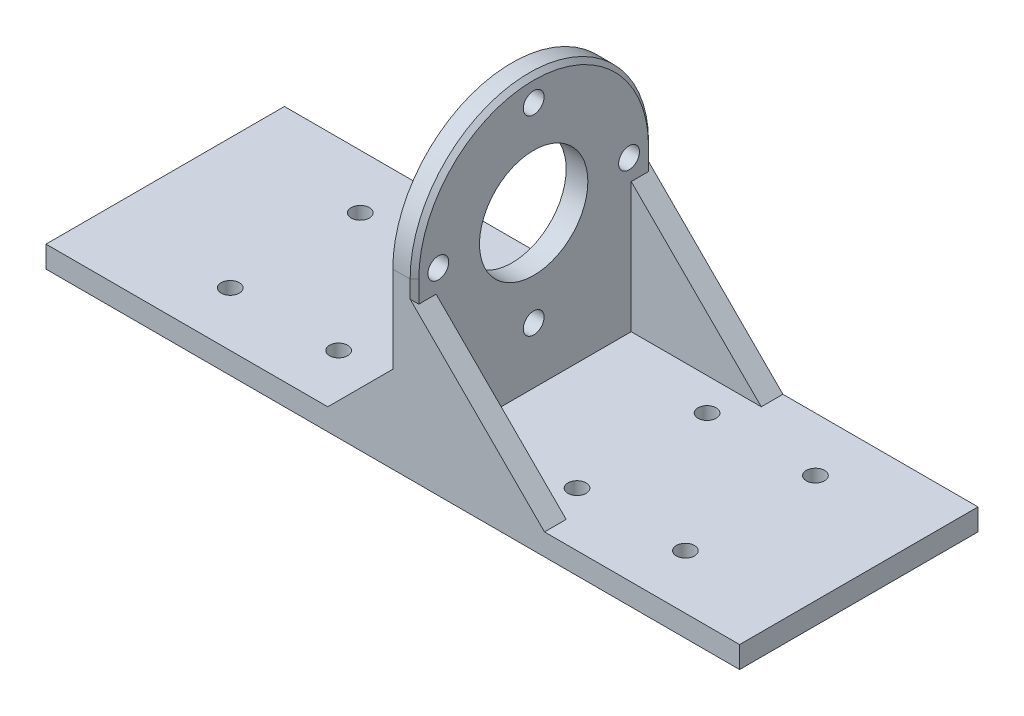
SolidWorks part; units mm, degrees
ref_plane "Front" through (0, 0, 0) normal (0, 0, 1) x (1, 0, 0)
ref_plane "Top" through (0, 0, 0) normal (0, 1, 0) x (1, 0, 0)
ref_plane "Right" through (0, 0, 0) normal (1, 0, 0) x (0, 0, -1)
sketch "草图1" plane through (0, 0, 0) normal (1, 0, 0) x (0, 0, -1)
  line L0 (-27.5, 0) -> (-27.5, -40)
  line L1 (-27.5, -40) -> (27.5, -40)
  line L2 (27.5, -40) -> (27.5, 0)
  arc A0 (27.5, 0) -> (-27.5, 0) centre (0, 0) ccw
  circle A1 centre (0, 0) radius 22 construction
  circle A2 centre (0, 0) radius 12.5
  circle A3 centre (0, 22) radius 2.4
  circle A4 centre (22, 0) radius 2.4
  circle A5 centre (0, -22) radius 2.4
  circle A6 centre (-22, 0) radius 2.4
extrude "凸台-拉伸1" add sketch "草图1" along normal blind 5
sketch "草图2" plane through (0, 0, 0) normal (-1, 0, 0) x (0, 0, 1)
  line L0 (27.5, 0) -> (27.5, -40) construction
  line L1 (-27.5, -40) -> (27.5, -40)
  line L2 (-27.5, -40) -> (-27.5, -35)
  line L3 (-27.5, -35) -> (27.5, -35)
  line L4 (27.5, -40) -> (27.5, -35)
  line L5 (0, -35) -> (0, -40) construction
  line L6 (-27.5, -37.5) -> (27.5, -37.5) construction
  point P112 (0, -37.5)
extrude "凸台-拉伸2" add sketch "草图2" along normal blind 80 contours L3 L4 L1 L2
sketch3d "3D草图1" plane through (0, 0, 0) normal (0, 0, 1) x (1, 0, 0)
  dimension "D1" = 25
sketch "草图3" plane through (0, 0, 25) normal (0, 0, 1) x (1, 0, 0)
  line L0 (0, -35) -> (0, -20) construction
  line L1 (0, 0) -> (0, -35) construction
  line L2 (0, -35) -> (-15, -35) construction
  line L3 (-80, -35) -> (0, -35) construction
  line L4 (-15, -35) -> (0, -20)
  dimension "D1" = 15
  dimension "D2" = 15
rib "筋1" sketch "草图3" sketch "草图3" thickness 5 extrusion direction parallel to sketch draft on no parameters "D1"=5
mirror "镜向1" about plane through (0, 0, 0) normal (0, 0, 1) of "筋1"
chamfer "倒角2" distance 5 angle 45 1 edges at (0, -35, 0)
sketch "草图4" plane through (5, 0, 0) normal (1, 0, 0) x (0, 0, -1)
  line L0 (27.5, -40) -> (27.5, 0) construction
  line L1 (-27.5, -40) -> (27.5, -40)
  line L2 (-27.5, -40) -> (-27.5, -35)
  line L3 (-27.5, -35) -> (27.5, -35)
  line L4 (27.5, -40) -> (27.5, -35)
  line L5 (0, -35) -> (0, -40) construction
  line L6 (-27.5, -37.5) -> (27.5, -37.5) construction
  point P160 (0, -37.5)
extrude "凸台-拉伸3" add sketch "草图4" along normal blind 75
sketch "草图5" plane through (0, 0, 25) normal (0, 0, 1) x (1, 0, 0)
  line L0 (5, -35) -> (5, -5) construction
  line L1 (5, 0) -> (5, -35) construction
  line L2 (5, -35) -> (35, -35) construction
  line L3 (80, -35) -> (5, -35) construction
  line L4 (35, -35) -> (5, -5)
rib "筋6" sketch "草图5" sketch "草图5" thickness 5 extrusion direction parallel to sketch draft on no parameters "D1"=5
mirror "镜向2" about plane through (0, 0, 0) normal (0, 0, 1) of "筋6"
sketch "草图6" plane through (0, -35, 0) normal (0, 1, 0) x (1, 0, 0)
  line L0 (5, 0) -> (5, 15) construction
  line L1 (5, 22.5) -> (5, -22.5) construction
  line L2 (5, 15) -> (80, 15) construction
  line L3 (80, 27.5) -> (80, -27.5) construction
  line L4 (5, 15) -> (-80, 15) construction
  line L5 (-80, 27.5) -> (-80, -27.5) construction
  line L6 (5, 15) -> (30, 15) construction
  line L7 (30, 15) -> (55, 15) construction
  line L8 (5, 15) -> (-25, 15) construction
  line L9 (-25, 15) -> (-50, 15) construction
  line L10 (0, 0) -> (20, 0) construction
  line L11 (-80, 27.5) -> (-15, 27.5) construction
  circle A0 centre (30, 15) radius 2.1
  circle A1 centre (55, 15) radius 2.1
  circle A2 centre (-50, 15) radius 2.1
  circle A3 centre (-25, 15) radius 2.1
  circle A4 centre (55, -15) radius 2.1
  circle A5 centre (30, -15) radius 2.1
  circle A6 centre (-25, -15) radius 2.1
  circle A7 centre (-50, -15) radius 2.1
  dimension "D1" = 30
  dimension "D2" = 25
  dimension "D3" = 25
  dimension "D4" = 25
  dimension "D5" = 12.5
extrude "切除-拉伸1" cut sketch "草图6" against normal up to next
chamfer "倒角3" distance 1 angle 45 3 edges at (5, -2.5, -27.5) (5, -2.5, 27.5) (5, 27.5, 0)
